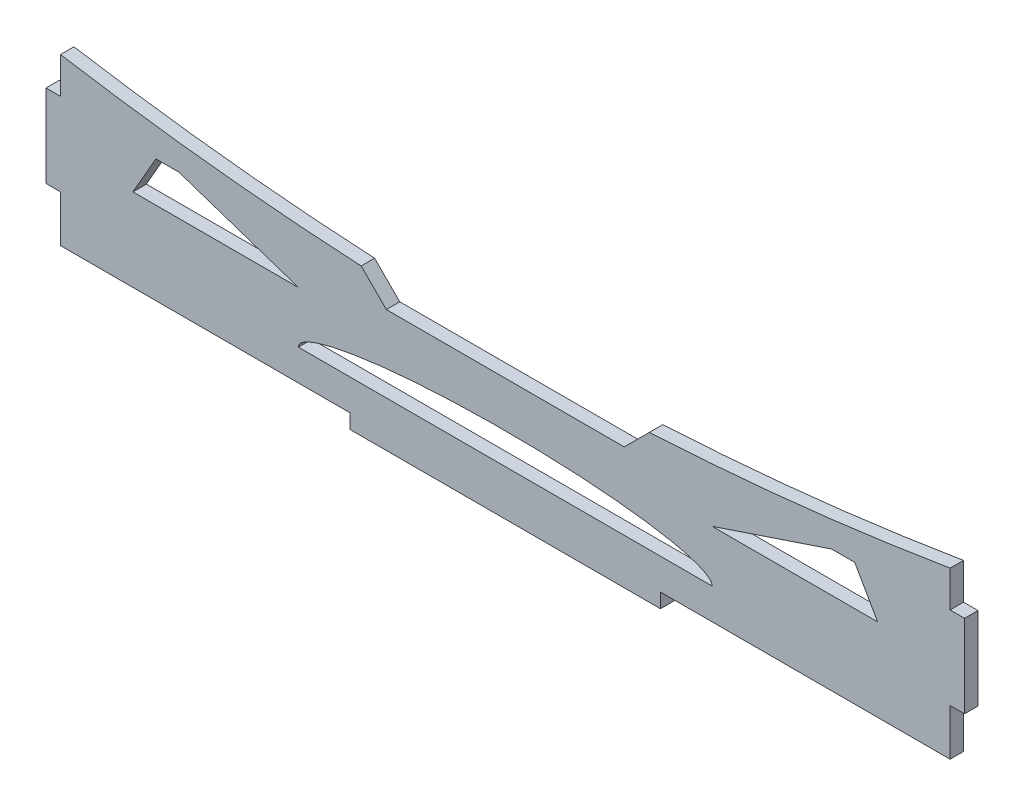
SolidWorks part; units mm, degrees
ref_plane "Front Plane" through (0, 0, 0) normal (0, 0, 1) x (1, 0, 0)
ref_plane "Top Plane" through (0, 0, 0) normal (0, 1, 0) x (1, 0, 0)
ref_plane "Right Plane" through (0, 0, 0) normal (1, 0, 0) x (0, 0, -1)
sketch "Sketch1" plane through (0, 0, 0) normal (0, 0, 1) x (1, 0, 0)
  line L1 (-43, 8) -> (43, 8)
  line L2 (-43, 8) -> (-43, -8)
  line L3 (-43, -8) -> (43, -8)
  line L4 (43, 8) -> (43, -8)
  line L5 (-43, 8) -> (43, -8) construction
  line L6 (-43, -8) -> (43, 8) construction
  point P0 (0, 0)
  dimension "D1" = 86
  dimension "D2" = 16
extrude "Boss-Extrude1" add sketch "Sketch1" along normal blind 1.3
sketch "Sketch2" plane through (0, 0, 1.3) normal (0, 0, 1) x (1, 0, 0)
  line L0 (-43, 8) -> (-43, -8) construction
  line L1 (-43, 4.5) -> (-44.4, 4.5)
  line L2 (-43, 4.5) -> (-43, -3.5)
  line L3 (-43, -3.5) -> (-44.4, -3.5)
  line L4 (-44.4, 4.5) -> (-44.4, -3.5)
  line L5 (43, -8) -> (43, 8) construction
  line L6 (43, 4.5) -> (44.4, 4.5)
  line L7 (43, 4.5) -> (43, -3.5)
  line L8 (43, -3.5) -> (44.4, -3.5)
  line L9 (44.4, 4.5) -> (44.4, -3.5)
  line L10 (-43, -8) -> (43, -8) construction
  line L11 (-15, -8) -> (15, -8)
  line L12 (-15, -8) -> (-15, -9.4)
  line L13 (-15, -9.4) -> (15, -9.4)
  line L14 (15, -8) -> (15, -9.4)
  line L15 (0, -0.715) -> (0, 0.715) construction
  dimension "D1" = 1.4
  dimension "D2" = 1.4
  dimension "D3" = 1.4
  dimension "D4" = 8
  dimension "D5" = 8
  dimension "D6" = 30
  dimension "D7" = 15
  dimension "D8" = 4.5
  dimension "D9" = 4.5
extrude "Boss-Extrude2" add sketch "Sketch2" against normal blind 1.3
sketch "Sketch3" plane through (0, 0, 1.3) normal (0, 0, 1) x (1, 0, 0)
  line L0 (-43, 8) -> (43, 8)
  line L1 (-20, 0) -> (-31.5557, 3.872)
  line L2 (0.715, 0) -> (-0.715, 0) construction
  line L3 (-31.5557, 3.872) -> (-33.7779, 3.872)
  line L4 (-33.7779, 3.872) -> (-36, 0)
  line L5 (-36, 0) -> (-20, 0)
  line L6 (0, -0.715) -> (0, 0.715) construction
  line L7 (36, 0) -> (20, 0)
  line L8 (33.7779, 3.872) -> (36, 0)
  line L9 (31.5557, 3.872) -> (33.7779, 3.872)
  line L10 (20, 0) -> (31.5557, 3.872)
  arc A0 (-43, 8) -> (43, 8) centre (0, 267.5304) ccw
  dimension "D1" = 20
  dimension "D2" = 16
extrude "Cut-Extrude1" cut sketch "Sketch3" against normal through all
sketch "Sketch4" plane through (0, 0, 1.3) normal (0, 0, 1) x (1, 0, 0)
  line L0 (-9, 0) -> (9, 0) construction
  line L1 (-13.931, 4.831) -> (-11.5, 2.4)
  line L2 (0.715, 0) -> (-0.715, 0) construction
  line L3 (-9, 0) -> (9, 0) construction
  line L4 (11.5, 2.4) -> (13.931, 4.831)
  line L5 (-13.931, 4.831) -> (13.931, 4.831)
  line L6 (0, -0.715) -> (0, 0.715) construction
  line L7 (-20, -5) -> (20, -5)
  line L8 (15, -8) -> (43, -8) construction
  line L9 (-11.5, 2.4) -> (11.5, 2.4)
  arc A2 (-43, 8) -> (43, 8) centre (0, 267.5304) ccw construction
  ellipse E0 centre (0, -5) end of major axis (20, -5) minor radius 3 (20, -5) -> (-20, -5) ccw
  dimension "D5" = 2.4
  dimension "D1" = 11.5
  dimension "D2" = 23
  dimension "D3" = 40
  dimension "D4" = 3
  dimension "D8" = 3
extrude "Cut-Extrude2" cut sketch "Sketch4" against normal through all
